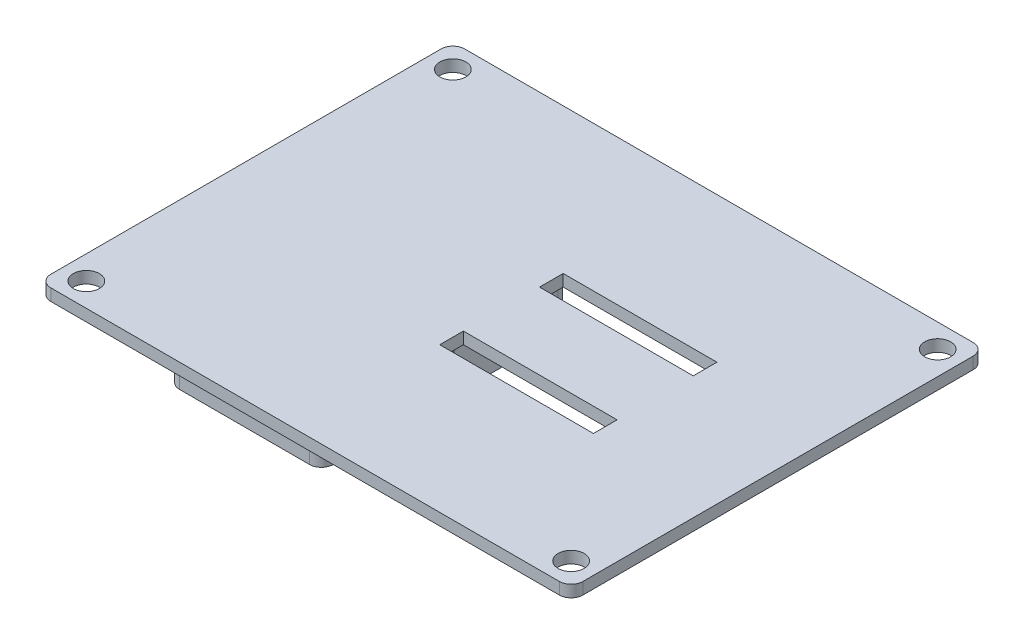
SolidWorks part; units mm, degrees
ref_plane "Front Plane" through (0, 0, 0) normal (0, 0, 1) x (1, 0, 0)
ref_plane "Top Plane" through (0, 0, 0) normal (0, 1, 0) x (1, 0, 0)
ref_plane "Right Plane" through (0, 0, 0) normal (1, 0, 0) x (0, 0, -1)
sketch "Sketch1" plane through (0, 0, 0) normal (0, 1, 0) x (1, 0, 0)
  line L1 (-57.15, -44.45) -> (57.15, -44.45)
  line L2 (-57.15, -44.45) -> (-57.15, 44.45)
  line L3 (-57.15, 44.45) -> (57.15, 44.45)
  line L4 (57.15, -44.45) -> (57.15, 44.45)
  line L5 (-57.15, -44.45) -> (57.15, 44.45) construction
  line L6 (-57.15, 44.45) -> (57.15, -44.45) construction
  point P0 (0, 0)
  dimension "D1" = 88.9
  dimension "D2" = 114.3
extrude "Boss-Extrude2" add sketch "Sketch1" along normal blind 2.54
sketch "Sketch2" plane through (0, 0, 0) normal (0, -1, 0) x (-1, 0, 0)
  line L1 (-52.07, 39.37) -> (52.07, 39.37)
  line L2 (-52.07, 39.37) -> (-52.07, -39.37)
  line L3 (-52.07, -39.37) -> (52.07, -39.37)
  line L4 (52.07, 39.37) -> (52.07, -39.37)
  line L5 (-52.07, 39.37) -> (52.07, -39.37) construction
  line L6 (-52.07, -39.37) -> (52.07, 39.37) construction
  circle A0 centre (52.07, 39.37) radius 2.794
  circle A1 centre (52.07, -39.37) radius 2.794
  circle A2 centre (-52.07, -39.37) radius 2.794
  circle A3 centre (-52.07, 39.37) radius 2.794
  point P0 (0, 0)
  dimension "D3" = 5.588
  dimension "D4" = 5.588
  dimension "D5" = 5.588
  dimension "D6" = 5.588
  dimension "D1" = 104.14
  dimension "D2" = 78.74
extrude "Cut-Extrude1" cut sketch "Sketch2" against normal blind 5.08 contours A0 | A1 | A2 | A3
sketch "Sketch8" plane through (0, 0, 0) normal (0, -1, 0) x (-1, 0, 0)
  line L1 (48.5659, -25.4) -> (15.5459, -25.4)
  line L2 (48.5659, -25.4) -> (48.5659, 27.94)
  line L3 (48.5659, 27.94) -> (15.5459, 27.94)
  line L4 (15.5459, -25.4) -> (15.5459, 27.94)
  line L5 (48.5659, -25.4) -> (15.5459, 27.94) construction
  line L6 (48.5659, 27.94) -> (15.5459, -25.4) construction
  point P0 (32.0559, 1.27)
  dimension "D1" = 33.02
  dimension "D2" = 53.34
sketch "Sketch9" plane through (0, 0, 0) normal (0, -1, 0) x (-1, 0, 0)
  line L0 (0, 44.45) -> (0, -44.45) construction
  line L1 (-57.15, 44.45) -> (57.15, 44.45) construction
  line L2 (57.15, -44.45) -> (-57.15, -44.45) construction
  line L3 (-57.15, 0) -> (57.15, 0) construction
  line L4 (-57.15, -44.45) -> (-57.15, 44.45) construction
  line L5 (57.15, 44.45) -> (57.15, -44.45) construction
  line L6 (2.2645, -13.2599) -> (2.2645, -8.1799)
  line L7 (-30.7555, 13.2599) -> (2.2645, 13.2599)
  line L8 (-30.7555, 13.2599) -> (-30.7555, 8.1799)
  line L9 (-30.7555, 8.1799) -> (2.2645, 8.1799)
  line L10 (2.2645, 13.2599) -> (2.2645, 8.1799)
  line L11 (-30.7555, 13.2599) -> (2.2645, 8.1799) construction
  line L12 (-30.7555, 8.1799) -> (2.2645, 13.2599) construction
  line L13 (-30.7555, -8.1799) -> (2.2645, -8.1799)
  line L14 (-30.7555, -13.2599) -> (-30.7555, -8.1799)
  line L15 (-30.7555, -13.2599) -> (2.2645, -13.2599)
  point P12 (-14.2455, 10.7199)
  dimension "D1" = 33.02
  dimension "D2" = 5.08
extrude "Cut-Extrude5" cut sketch "Sketch9" against normal blind 6.35
extrude "Boss-Extrude4" add sketch "Sketch8" along normal blind 21.59 separate body
shell "Shell4" thickness 2.54
sketch "Sketch13" plane through (0, 0, -27.94) normal (0, 0, -1) x (-1, 0, 0)
  line L0 (32.0559, 0) -> (32.0559, -21.59) construction
  line L1 (48.5659, 0) -> (15.5459, 0) construction
  line L2 (48.5659, -21.59) -> (15.5459, -21.59) construction
  line L3 (48.5659, -10.795) -> (15.5459, -10.795) construction
  line L4 (48.5659, -21.59) -> (48.5659, 0) construction
  line L5 (15.5459, -21.59) -> (15.5459, 0) construction
  line L7 (44.3624, -3.7461) -> (19.7495, -3.7461)
  line L8 (44.3624, -3.7461) -> (44.3624, -17.8439)
  line L9 (44.3624, -17.8439) -> (19.7495, -17.8439)
  line L10 (19.7495, -3.7461) -> (19.7495, -17.8439)
  line L11 (44.3624, -3.7461) -> (19.7495, -17.8439) construction
  line L12 (44.3624, -17.8439) -> (19.7495, -3.7461) construction
  point P12 (32.0559, -10.795)
extrude "Cut-Extrude6" cut sketch "Sketch13" against normal blind 5.08
fillet "Fillet5" radius 2.54 1 edges at (-19.7495, -17.8439, -26.67)
fillet "Fillet6" radius 2.54 1 edges at (-19.7495, -3.7461, -26.67)
fillet "Fillet7" radius 2.54 1 edges at (-44.3624, -3.7461, -26.67)
fillet "Fillet8" radius 2.54 1 edges at (-44.3624, -17.8439, -26.67)
fillet "Fillet1" radius 2.54 1 edges at (57.15, 1.27, 44.45)
fillet "Fillet2" radius 2.54 1 edges at (-57.15, 1.27, -44.45)
fillet "Fillet3" radius 2.54 1 edges at (-57.15, 1.27, 44.45)
fillet "Fillet4" radius 2.54 1 edges at (57.15, 1.27, -44.45)
fillet "Fillet9" radius 2.54 1 edges at (-15.5459, -10.795, -27.94)
fillet "Fillet10" radius 2.54 1 edges at (-15.5459, -10.795, 25.4)
fillet "Fillet11" radius 2.54 1 edges at (-48.5659, -10.795, 25.4)
fillet "Fillet12" radius 2.54 1 edges at (-48.5659, -10.795, -27.94)
sketch "Sketch17" plane through (0, 0, 0) normal (0, -1, 0) x (-1, 0, 0)
  line L0 (-57.15, 37.465) -> (57.15, 37.465) construction
  line L1 (-57.15, -41.91) -> (-57.15, 41.91) construction
  line L2 (57.15, 41.91) -> (57.15, -41.91) construction
  line L3 (-54.61, 44.45) -> (54.61, 44.45) construction
  line L5 (-37.0749, 37.465) -> (8.6451, 37.465) construction
  line L6 (-37.0749, 37.465) -> (-37.0749, -8.255) construction
  line L7 (-37.0749, -8.255) -> (8.6451, -8.255) construction
  line L8 (8.6451, 37.465) -> (8.6451, -8.255) construction
  line L9 (-37.0749, 37.465) -> (8.6451, -8.255) construction
  line L10 (-37.0749, -8.255) -> (8.6451, 37.465) construction
  circle A0 centre (8.6451, -8.255) radius 3.175
  circle A1 centre (8.6451, 37.465) radius 3.175
  circle A2 centre (-37.0749, 37.465) radius 3.175
  circle A3 centre (-37.0749, -8.255) radius 3.175
  point P12 (-14.2149, 14.605)
  point P18 (-37.0749, -8.255)
  point P19 (-37.0749, 37.465)
  point P20 (8.6451, 37.465)
  point P21 (8.6451, -8.255)
  point P22 (-37.0749, -8.255)
  point P23 (-37.0749, 37.465)
  point P24 (8.6451, -8.255)
  point P25 (8.6451, 37.465)
  dimension "D4" = 6.35
  dimension "D5" = 6.35
  dimension "D6" = 6.35
  dimension "D7" = 6.35
  dimension "D1" = 6.985
  dimension "D2" = 45.72
  dimension "D3" = 45.72
extrude "Boss-Extrude5" add sketch "Sketch17" along normal blind 7.62
sketch "Sketch18" plane through (0, -7.62, 0) normal (0, -1, 0) x (1, 0, 0)
  circle A0 centre (37.0749, 8.255) radius 1.651
  circle A1 centre (37.0749, -37.465) radius 1.651
  circle A2 centre (-8.6451, -37.465) radius 1.651
  circle A3 centre (-8.6451, 8.255) radius 1.651
  point P0 (-8.6451, 8.255)
  point P1 (-8.6451, -37.465)
  point P3 (37.0749, -37.465)
  point P5 (37.0749, 8.255)
  dimension "D1" = 3.302
  dimension "D2" = 3.302
  dimension "D3" = 3.302
  dimension "D4" = 3.302
extrude "Cut-Extrude7" cut sketch "Sketch18" against normal blind 5.08 draft 2 contours A0 | A1 | A2 | A3
